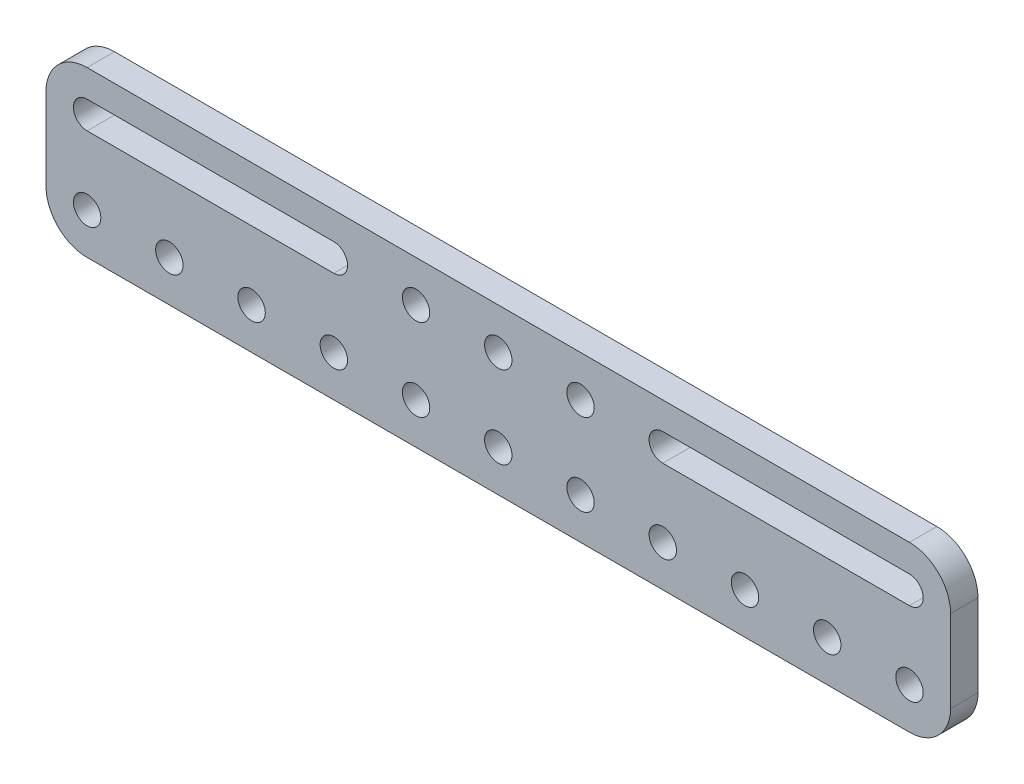
SolidWorks part; units mm, degrees
ref_plane "Alzado" through (0, 0, 0) normal (0, 0, 1) x (1, 0, 0)
ref_plane "Planta" through (0, 0, 0) normal (0, 1, 0) x (1, 0, 0)
ref_plane "Vista lateral" through (0, 0, 0) normal (1, 0, 0) x (0, 0, -1)
sketch "Model" plane through (0, 0, 0) normal (0, 0, 1) x (1, 0, 0)
  line L0 (256.4291, 228.7422) -> (346.4291, 228.7422)
  line L1 (346.4291, 210.7422) -> (256.4291, 210.7422)
  line L2 (350.9291, 224.2422) -> (350.9291, 215.2422)
  line L3 (251.9291, 224.2422) -> (251.9291, 215.2422)
  line L4 (256.4291, 225.7422) -> (283.4291, 225.7422)
  line L5 (256.4291, 222.7422) -> (283.4291, 222.7422)
  line L6 (319.4291, 225.7422) -> (346.4291, 225.7422)
  line L7 (346.4291, 222.7422) -> (319.4291, 222.7422)
  arc A0 (350.9291, 224.2422) -> (346.4291, 228.7422) centre (346.4291, 224.2422) ccw
  arc A1 (256.4291, 228.7422) -> (251.9291, 224.2422) centre (256.4291, 224.2422) ccw
  arc A2 (251.9291, 215.2422) -> (256.4291, 210.7422) centre (256.4291, 215.2422) ccw
  arc A3 (346.4291, 210.7422) -> (350.9291, 215.2422) centre (346.4291, 215.2422) ccw
  circle A4 centre (310.4291, 224.2422) radius 1.5
  circle A5 centre (292.4291, 224.2422) radius 1.5
  circle A6 centre (301.4291, 224.2422) radius 1.5
  circle A7 centre (337.4291, 215.2422) radius 1.5
  circle A8 centre (319.4291, 215.2422) radius 1.5
  circle A9 centre (328.4291, 215.2422) radius 1.5
  circle A10 centre (310.4291, 215.2422) radius 1.5
  circle A11 centre (292.4291, 215.2422) radius 1.5
  circle A12 centre (301.4291, 215.2422) radius 1.5
  circle A13 centre (274.4291, 215.2422) radius 1.5
  circle A14 centre (283.4291, 215.2422) radius 1.5
  circle A15 centre (265.4291, 215.2422) radius 1.5
  circle A16 centre (256.4291, 215.2422) radius 1.5
  circle A17 centre (346.4291, 215.2422) radius 1.5
  arc A18 (256.4291, 225.7422) -> (256.4291, 222.7422) centre (256.4291, 224.2422) ccw
  arc A19 (283.4291, 222.7422) -> (283.4291, 225.7422) centre (283.4291, 224.2422) ccw
  arc A20 (346.4291, 222.7422) -> (346.4291, 225.7422) centre (346.4291, 224.2422) ccw
  arc A21 (319.4291, 225.7422) -> (319.4291, 222.7422) centre (319.4291, 224.2422) ccw
extrude "Saliente-Extruir1" add sketch "Model" along normal blind 3
